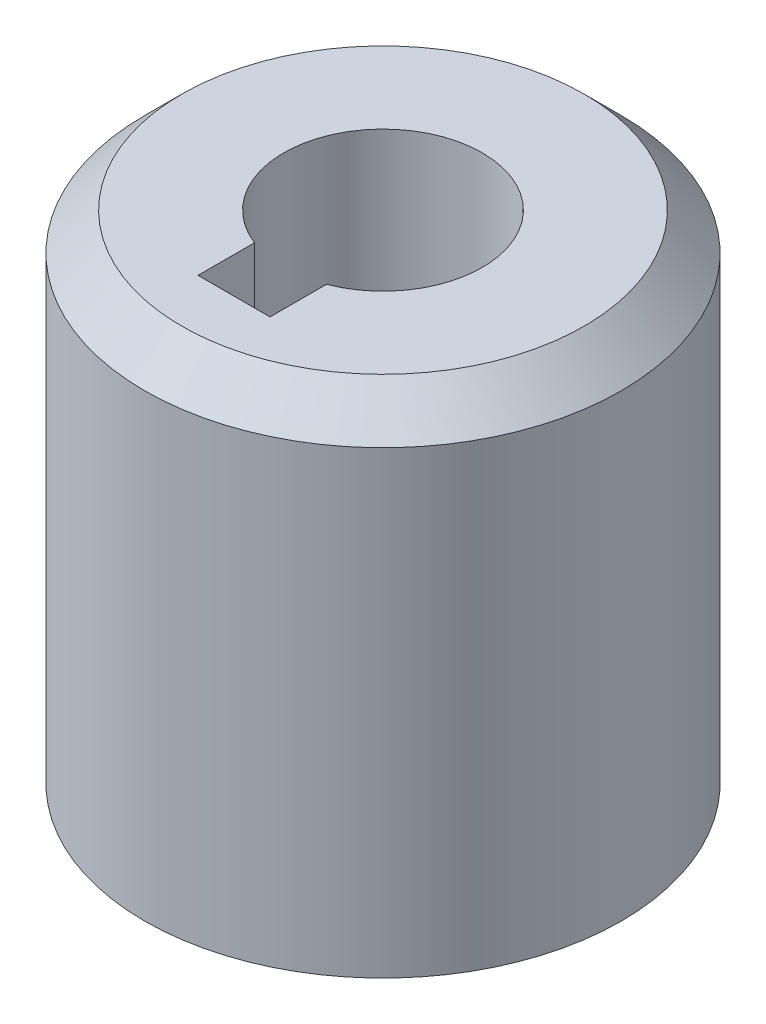
SolidWorks part; units mm, degrees
ref_plane "Front Plane" through (0, 0, 0) normal (0, 0, 1) x (1, 0, 0)
ref_plane "Top Plane" through (0, 0, 0) normal (0, 1, 0) x (1, 0, 0)
ref_plane "Right Plane" through (0, 0, 0) normal (1, 0, 0) x (0, 0, -1)
sketch "Sketch1" plane through (0, 0, 0) normal (0, 1, 0) x (1, 0, 0)
  line L1 (-1.45, -6) -> (1.45, -6)
  line L5 (0, -6) -> (0, -4) construction
  line L8 (-1.45, -6) -> (-1.45, -3.7279)
  line L10 (1.45, -6) -> (1.45, -3.7279)
  circle A0 centre (0, 0) radius 9.6
  arc A1 (1.45, -3.7279) -> (-1.45, -3.7279) centre (0, 0) ccw
  circle A2 centre (0, 0) radius 4 construction
  dimension "D1" = 19.2
  dimension "D2" = 8
  dimension "D3" = 6
  dimension "D4" = 2.9
extrude "Boss-Extrude1" add sketch "Sketch1" along normal blind 20
chamfer "Chamfer1" distance 1.5 angle 45 1 edges at (0, 20, 9.6)
